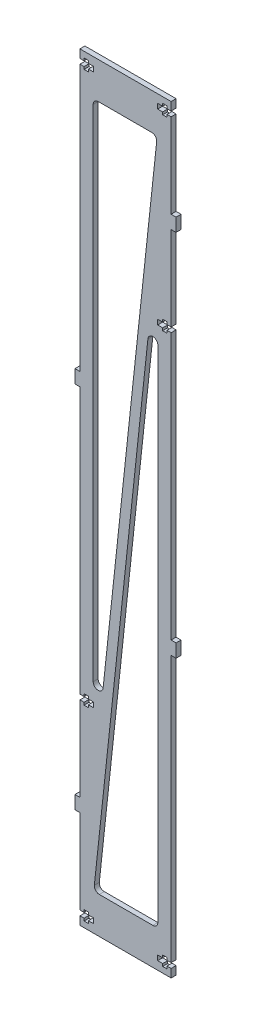
SolidWorks part; units mm, degrees
ref_plane "前视基准面" through (0, 0, 0) normal (0, 0, 1) x (1, 0, 0)
ref_plane "上视基准面" through (0, 0, 0) normal (0, 1, 0) x (1, 0, 0)
ref_plane "右视基准面" through (0, 0, 0) normal (1, 0, 0) x (0, 0, -1)
sketch "草图1" plane through (0, 0, 0) normal (0, 0, 1) x (1, 0, 0)
  line L261 (277.4534, -198.0371) -> (277.4534, -203.0371)
  line L264 (272.4534, 235.9629) -> (272.4534, -184.0371) construction
  line L265 (272.4534, -184.0371) -> (227.4534, -184.0371) construction
  line L266 (227.4534, -184.0371) -> (227.4534, 235.9629) construction
  line L267 (227.4534, 235.9629) -> (272.4534, 235.9629) construction
  line L268 (272.4534, 235.9629) -> (227.4534, -184.0371) construction
  line L270 (233.4534, 232.9629) -> (265.7762, 232.9629)
  line L271 (268.7591, 229.6433) -> (236.4363, -72.0362)
  line L272 (230.4534, -71.7166) -> (230.4534, 229.9629)
  line L273 (269.4534, 123.6424) -> (269.4534, -178.0371)
  line L274 (266.4534, -181.0371) -> (234.1306, -181.0371)
  line L275 (263.4704, 123.962) -> (231.1476, -177.7175)
  line L276 (269.4534, 179.8027) -> (269.4534, -181.0371) construction
  line L277 (269.4534, -181.0371) -> (230.792, -181.0371) construction
  line L278 (269.4534, 179.8027) -> (230.792, -181.0371) construction
  line L279 (230.4534, -127.8768) -> (230.4534, 232.9629) construction
  line L280 (269.1148, 232.9629) -> (230.4534, -127.8768) construction
  line L281 (230.4534, 232.9629) -> (269.1148, 232.9629) construction
  line L282 (224.9534, -85.2166) -> (224.9534, -86.7166)
  line L283 (224.9534, -82.2166) -> (224.9534, -80.7166)
  line L284 (222.4534, -82.2166) -> (224.9534, -82.2166)
  line L285 (224.9534, -86.7166) -> (227.5534, -86.7166)
  line L286 (227.5534, -86.7166) -> (227.5534, -85.2166)
  line L287 (227.5534, -85.2166) -> (230.5534, -85.2166)
  line L288 (230.5534, -82.2166) -> (230.5534, -85.2166)
  line L289 (227.5534, -82.2166) -> (230.5534, -82.2166)
  line L290 (227.5534, -80.7166) -> (227.5534, -82.2166)
  line L291 (224.9534, -80.7166) -> (227.5534, -80.7166)
  line L292 (224.9534, -85.2166) -> (222.4534, -85.2166)
  line L293 (230.5534, -83.7166) -> (222.4534, -83.7166) construction
  line L294 (233.4534, -71.7166) -> (233.4534, -83.7166) construction
  line L295 (233.4534, -83.7166) -> (222.4534, -83.7166) construction
  line L296 (249.9534, -196.5371) -> (222.4534, -196.5371) construction
  line L297 (249.9534, 248.4629) -> (222.4534, 248.4629) construction
  line L298 (224.9534, -198.0371) -> (224.9534, -199.5371)
  line L299 (224.9534, -195.0371) -> (224.9534, -193.5371)
  line L300 (222.4534, -195.0371) -> (224.9534, -195.0371)
  line L301 (224.9534, -199.5371) -> (227.5534, -199.5371)
  line L302 (227.5534, -199.5371) -> (227.5534, -198.0371)
  line L303 (227.5534, -198.0371) -> (230.5534, -198.0371)
  line L304 (230.5534, -195.0371) -> (230.5534, -198.0371)
  line L305 (227.5534, -195.0371) -> (230.5534, -195.0371)
  line L306 (227.5534, -193.5371) -> (227.5534, -195.0371)
  line L307 (224.9534, -193.5371) -> (227.5534, -193.5371)
  line L308 (224.9534, -198.0371) -> (222.4534, -198.0371)
  line L309 (230.5534, -196.5371) -> (222.4534, -196.5371) construction
  line L310 (224.9534, 246.9629) -> (224.9534, 245.4629)
  line L311 (224.9534, 249.9629) -> (224.9534, 251.4629)
  line L312 (222.4534, 249.9629) -> (224.9534, 249.9629)
  line L313 (224.9534, 245.4629) -> (227.5534, 245.4629)
  line L314 (227.5534, 245.4629) -> (227.5534, 246.9629)
  line L315 (227.5534, 246.9629) -> (230.5534, 246.9629)
  line L316 (230.5534, 249.9629) -> (230.5534, 246.9629)
  line L317 (227.5534, 249.9629) -> (230.5534, 249.9629)
  line L318 (227.5534, 251.4629) -> (227.5534, 249.9629)
  line L319 (224.9534, 251.4629) -> (227.5534, 251.4629)
  line L320 (224.9534, 246.9629) -> (222.4534, 246.9629)
  line L321 (230.5534, 248.4629) -> (222.4534, 248.4629) construction
  line L326 (277.4534, -195.0371) -> (274.9534, -195.0371)
  line L327 (274.9534, -195.0371) -> (274.9534, -193.5371)
  line L328 (274.9534, -193.5371) -> (272.3534, -193.5371)
  line L329 (272.3534, -193.5371) -> (272.3534, -195.0371)
  line L330 (272.3534, -195.0371) -> (269.3534, -195.0371)
  line L331 (269.3534, -195.0371) -> (269.3534, -198.0371)
  line L332 (272.3534, -198.0371) -> (269.3534, -198.0371)
  line L333 (274.9534, -199.5371) -> (272.3534, -199.5371)
  line L334 (272.3534, -199.5371) -> (272.3534, -198.0371)
  line L335 (274.9534, -198.0371) -> (274.9534, -199.5371)
  line L336 (274.9534, -198.0371) -> (277.4534, -198.0371)
  line L337 (272.3534, 249.9629) -> (269.3534, 249.9629)
  line L338 (269.3534, 249.9629) -> (269.3534, 246.9629)
  line L339 (272.3534, 246.9629) -> (269.3534, 246.9629)
  line L340 (272.3534, 245.4629) -> (272.3534, 246.9629)
  line L341 (274.9534, 245.4629) -> (272.3534, 245.4629)
  line L342 (274.9534, 246.9629) -> (274.9534, 245.4629)
  line L343 (274.9534, 246.9629) -> (277.4534, 246.9629)
  line L344 (277.4534, 249.9629) -> (274.9534, 249.9629)
  line L345 (274.9534, 249.9629) -> (274.9534, 251.4629)
  line L346 (274.9534, 251.4629) -> (272.3534, 251.4629)
  line L347 (272.3534, 251.4629) -> (272.3534, 249.9629)
  line L348 (266.4534, 123.6424) -> (266.4534, 135.6424) construction
  line L349 (274.9534, 137.1424) -> (274.9534, 138.6424)
  line L350 (274.9534, 134.1424) -> (274.9534, 132.6424)
  line L351 (277.4534, 134.1424) -> (274.9534, 134.1424)
  line L352 (274.9534, 138.6424) -> (272.3534, 138.6424)
  line L353 (272.3534, 138.6424) -> (272.3534, 137.1424)
  line L354 (272.3534, 137.1424) -> (269.3534, 137.1424)
  line L355 (269.3534, 134.1424) -> (269.3534, 137.1424)
  line L356 (272.3534, 134.1424) -> (269.3534, 134.1424)
  line L357 (272.3534, 132.6424) -> (272.3534, 134.1424)
  line L358 (274.9534, 132.6424) -> (272.3534, 132.6424)
  line L359 (274.9534, 137.1424) -> (277.4534, 137.1424)
  line L360 (269.3534, 135.6424) -> (277.4534, 135.6424) construction
  line L361 (266.4534, 135.6424) -> (277.4534, 135.6424) construction
  line L378 (277.4534, -203.0371) -> (222.4534, -203.0371)
  line L395 (222.4534, -203.0371) -> (222.4534, -198.0371)
  line L407 (277.4534, 249.9629) -> (277.4534, 254.9629)
  line L410 (277.4534, 254.9629) -> (222.4534, 254.9629)
  line L411 (222.4534, 254.9629) -> (222.4534, 249.9629)
  line L412 (280.4534, 196.0527) -> (277.4534, 196.0527)
  line L413 (280.4534, 192.0527) -> (280.4534, 188.0527)
  line L414 (280.4534, 192.0527) -> (280.4534, 196.0527)
  line L415 (280.4534, 188.0527) -> (277.4534, 188.0527)
  line L416 (277.4534, 196.0527) -> (277.4534, 246.9629)
  line L417 (277.4534, 188.0527) -> (277.4534, 137.1424)
  line L418 (277.4534, -26.4473) -> (277.4534, 134.1424)
  line L419 (280.4534, -30.4473) -> (280.4534, -26.4473)
  line L420 (280.4534, -30.4473) -> (280.4534, -34.4473)
  line L421 (280.4534, -34.4473) -> (277.4534, -34.4473)
  line L422 (280.4534, -26.4473) -> (277.4534, -26.4473)
  line L423 (277.4534, -34.4473) -> (277.4534, -195.0371)
  line L424 (249.9534, 248.4629) -> (249.9534, 241.4742) construction
  line L425 (222.4534, 86.3732) -> (222.4534, 246.9629)
  line L426 (219.4534, 82.3732) -> (219.4534, 86.3732)
  line L427 (219.4534, 86.3732) -> (222.4534, 86.3732)
  line L428 (219.4534, 82.3732) -> (219.4534, 78.3732)
  line L429 (219.4534, 78.3732) -> (222.4534, 78.3732)
  line L430 (222.4534, 78.3732) -> (222.4534, -82.2166)
  line L431 (222.4534, -144.1268) -> (222.4534, -195.0371)
  line L432 (219.4534, -140.1268) -> (219.4534, -136.1268)
  line L433 (219.4534, -136.1268) -> (222.4534, -136.1268)
  line L434 (219.4534, -140.1268) -> (219.4534, -144.1268)
  line L435 (219.4534, -144.1268) -> (222.4534, -144.1268)
  line L436 (222.4534, -136.1268) -> (222.4534, -85.2166)
  arc A29 (269.4534, -178.0371) -> (266.4534, -181.0371) centre (266.4534, -178.0371) cw
  arc A30 (234.1306, -181.0371) -> (231.1476, -177.7175) centre (234.1306, -178.0371) cw
  arc A31 (269.4534, 123.6424) -> (263.4704, 123.962) centre (266.4534, 123.6424) ccw
  arc A32 (230.4534, -71.7166) -> (236.4363, -72.0362) centre (233.4534, -71.7166) ccw
  arc A33 (230.4534, 229.9629) -> (233.4534, 232.9629) centre (233.4534, 229.9629) cw
  arc A34 (268.7591, 229.6433) -> (265.7762, 232.9629) centre (265.7762, 229.9629) ccw
  dimension "D7" = 3
extrude "凸台-拉伸1" add sketch "草图1" along normal blind 3
sketch "草图2" plane through (277.4534, 0, 0) normal (1, 0, 0) x (0, 0, -1)
  line L0 (-1.5, 246.9629) -> (-1.5, 249.9629)
  line L1 (-3, 246.9629) -> (0, 246.9629) construction
  line L2 (-3, 249.9629) -> (0, 249.9629) construction
  circle A0 centre (-1.5, 248.4629) radius 1.5
